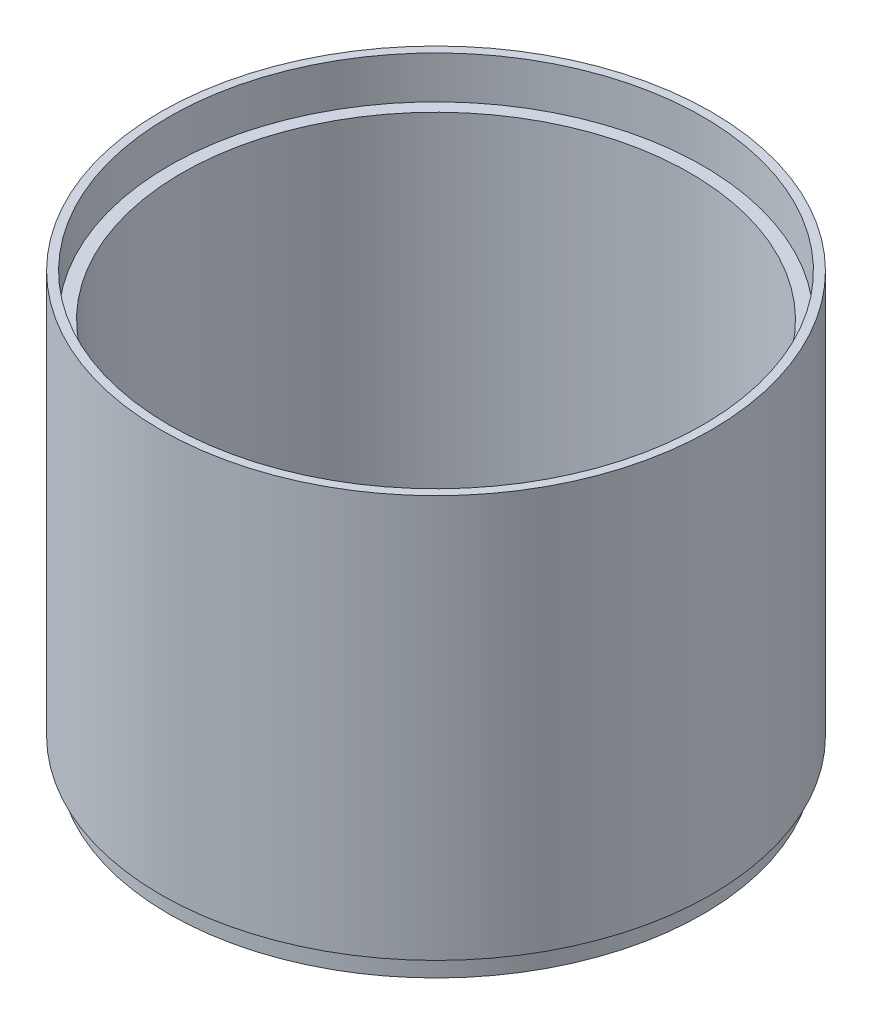
SolidWorks part; units mm, degrees
material "HYPALON"
ref_plane "Front Plane" through (0, 0, 0) normal (0, 0, 1) x (1, 0, 0)
ref_plane "Top Plane" through (0, 0, 0) normal (0, 1, 0) x (1, 0, 0)
ref_plane "Right Plane" through (0, 0, 0) normal (1, 0, 0) x (0, 0, -1)
sketch "Szkic1" plane through (0, 0, 0) normal (0, 0, 1) x (1, 0, 0)
  line L0 (-63, 0) -> (0, 0)
  line L1 (-63, 0) -> (-60, 0)
  line L2 (-63, 0) -> (-63, 5)
  line L3 (-63, 5) -> (-65, 5)
  line L4 (-65, 5) -> (-65, 28.5618)
  line L5 (-60, 0) -> (-60, 90)
  line L6 (-60, 90) -> (-63, 90)
  line L7 (-63, 90) -> (-63, 100)
  line L8 (-63, 100) -> (-65, 100)
  line L9 (-65, 100) -> (-65, 28.5618)
  line L10 (0, 35.541) -> (0, 0)
  dimension "D1" = 65
  dimension "D2" = 5
  dimension "D3" = 2
  dimension "D4" = 10
  dimension "D5" = 2
  dimension "D6" = 5
  dimension "D7" = 60
  dimension "D8" = 90
revolve "Obrót1" add sketch "Szkic1" angle 360 about L10
